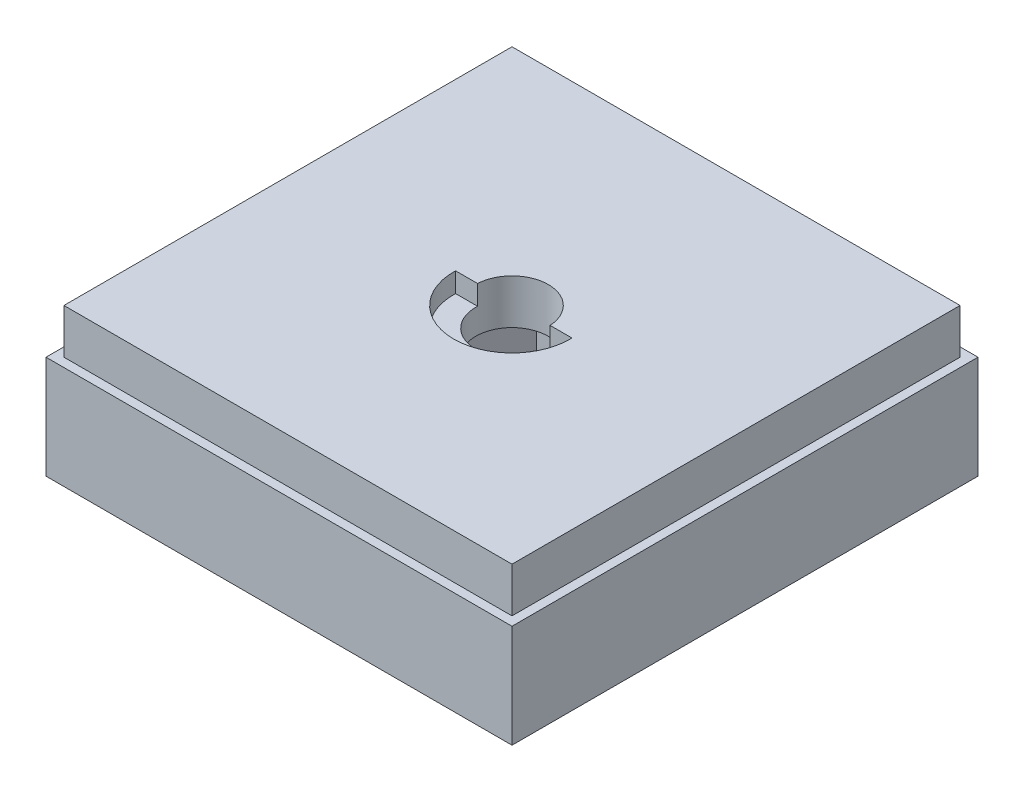
SolidWorks part; units mm, degrees
ref_plane "Front Plane" through (0, 0, 0) normal (0, 0, 1) x (1, 0, 0)
ref_plane "Top Plane" through (0, 0, 0) normal (0, 1, 0) x (1, 0, 0)
ref_plane "Right Plane" through (0, 0, 0) normal (1, 0, 0) x (0, 0, -1)
sketch "Sketch1" plane through (0, 0, 0) normal (0, 1, 0) x (1, 0, 0)
  line L0 (-52, 52) -> (0, 0) construction
  line L1 (-52, 52) -> (0, 52)
  line L2 (-52, 52) -> (-52, 0)
  line L3 (-52, 0) -> (0, 0)
  line L4 (0, 52) -> (0, 0)
  line L6 (-18.4944, 26) -> (-22.2472, 32.5)
  line L7 (-22.2472, 32.5) -> (-29.7528, 32.5)
  line L8 (-29.7528, 32.5) -> (-33.5056, 26)
  line L9 (-33.5056, 26) -> (-29.7528, 19.5)
  line L10 (-29.7528, 19.5) -> (-22.2472, 19.5)
  line L11 (-22.2472, 19.5) -> (-18.4944, 26)
  circle A0 centre (-26, 26) radius 6.5 construction
  dimension "D1" = 52
  dimension "D2" = 52
  dimension "D3" = 13
extrude "Boss-Extrude1" add sketch "Sketch1" along normal blind 11.5
sketch "Sketch2" plane through (0, 11.5, 0) normal (0, 1, 0) x (1, 0, 0)
  line L4 (-51, 51) -> (-1, 1) construction
  line L8 (-51, 51) -> (-51, 1)
  line L9 (-51, 1) -> (-1, 1)
  line L10 (-1, 1) -> (-1, 51)
  line L11 (-1, 51) -> (-51, 51)
  line L12 (-51, 51) -> (-51, 1)
  line L13 (-51, 1) -> (-1, 1)
  line L14 (-1, 1) -> (-1, 51)
  line L15 (-1, 51) -> (-51, 51)
  circle A0 centre (-26, 26) radius 4.05
  dimension "8.1" = 8.1
  dimension "D1" = 1
extrude "Boss-Extrude2" add sketch "Sketch2" along normal blind 5
sketch "Sketch3" plane through (0, 0, 0) normal (0, -1, 0) x (1, 0, 0)
  circle A0 centre (-26, -26) radius 8
  dimension "D1" = 16
extrude "Cut-Extrude1" cut sketch "Sketch3" against normal blind 7
sketch "Sketch4" plane through (0, 16.5, 0) normal (0, 1, 0) x (1, 0, 0)
  line L0 (-32.5, 26) -> (-19.5, 26) construction
  line L1 (-32.4969, 26.2) -> (-19.5031, 26.2)
  arc A0 (-32.4969, 26.2) -> (-19.5031, 26.2) centre (-26, 26) ccw
  dimension "D1" = 13
  dimension "D2" = 0.2
extrude "Cut-Extrude2" cut sketch "Sketch4" against normal blind 2.2
